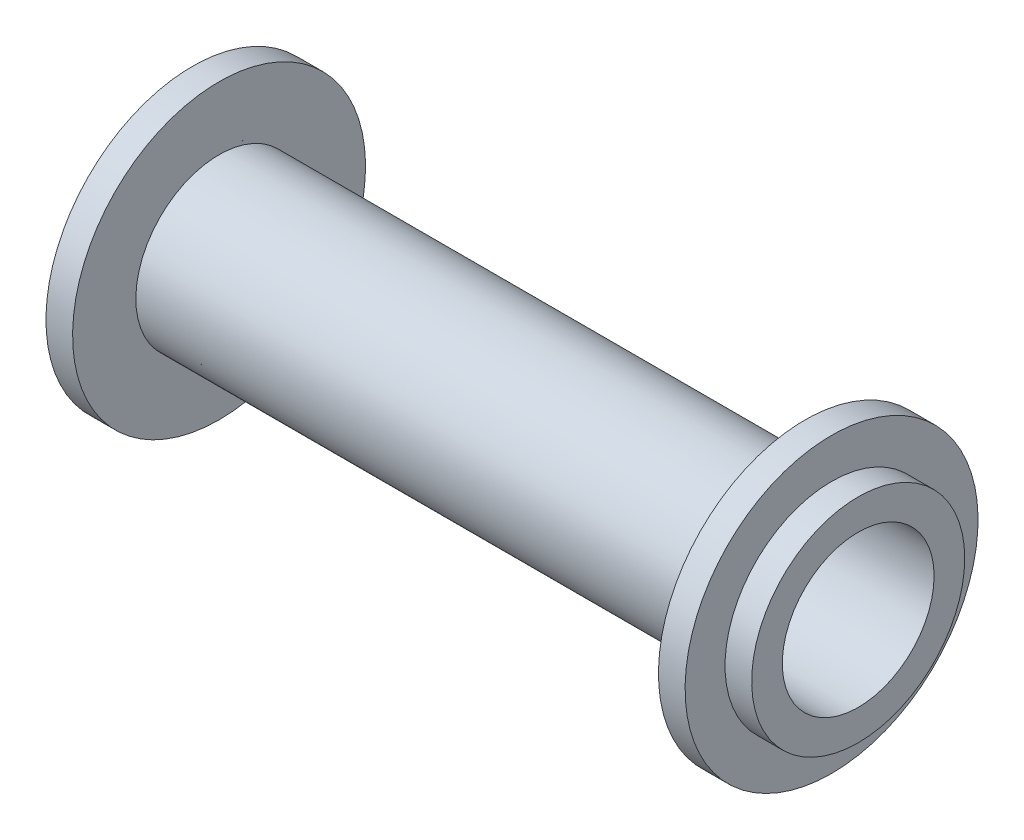
SolidWorks part; units mm, degrees
ref_plane "Front Plane" through (0, 0, 0) normal (0, 0, 1) x (1, 0, 0)
ref_plane "Top Plane" through (0, 0, 0) normal (0, 1, 0) x (1, 0, 0)
ref_plane "Right Plane" through (0, 0, 0) normal (1, 0, 0) x (0, 0, -1)
sketch "Sketch1" plane through (0, 0, 0) normal (0, 0, 1) x (1, 0, 0)
  line L0 (-24, 0) -> (24, 0)
  line L1 (-24, 0) -> (-24, 11)
  line L2 (-24, 11) -> (-22, 11)
  line L3 (-22, 11) -> (-22, 6.25)
  line L4 (0, 17.4375) -> (0, -6.8117) construction
  line L5 (-22, 6.25) -> (22, 6.25)
  line L6 (22, 11) -> (22, 6.25)
  line L7 (24, 0) -> (24, 11)
  line L8 (24, 11) -> (22, 11)
  point P10 (0, 0)
  point P11 (0, 6.25)
  dimension "D1" = 48
revolve "Revolve1" add sketch "Sketch1" angle 360 about L0
sketch "Sketch2" plane through (24, 0, 0) normal (1, 0, 0) x (0, 0, -1)
  circle A0 centre (0, 0) radius 5.7
extrude "Cut-Extrude1" cut sketch "Sketch2" against normal through all
sketch "Sketch3" plane through (24, 0, 0) normal (1, 0, 0) x (0, 0, -1)
  circle A0 centre (0, 0) radius 5.7
  circle A1 centre (0, 0) radius 8
extrude "Boss-Extrude1" add sketch "Sketch3" along normal blind 2
sketch "Sketch4" plane through (-24, 0, 0) normal (-1, 0, 0) x (0, 0, 1)
  circle A0 centre (0, 0) radius 5.7
  circle A1 centre (0, 0) radius 8
extrude "Boss-Extrude2" add sketch "Sketch4" along normal blind 2
